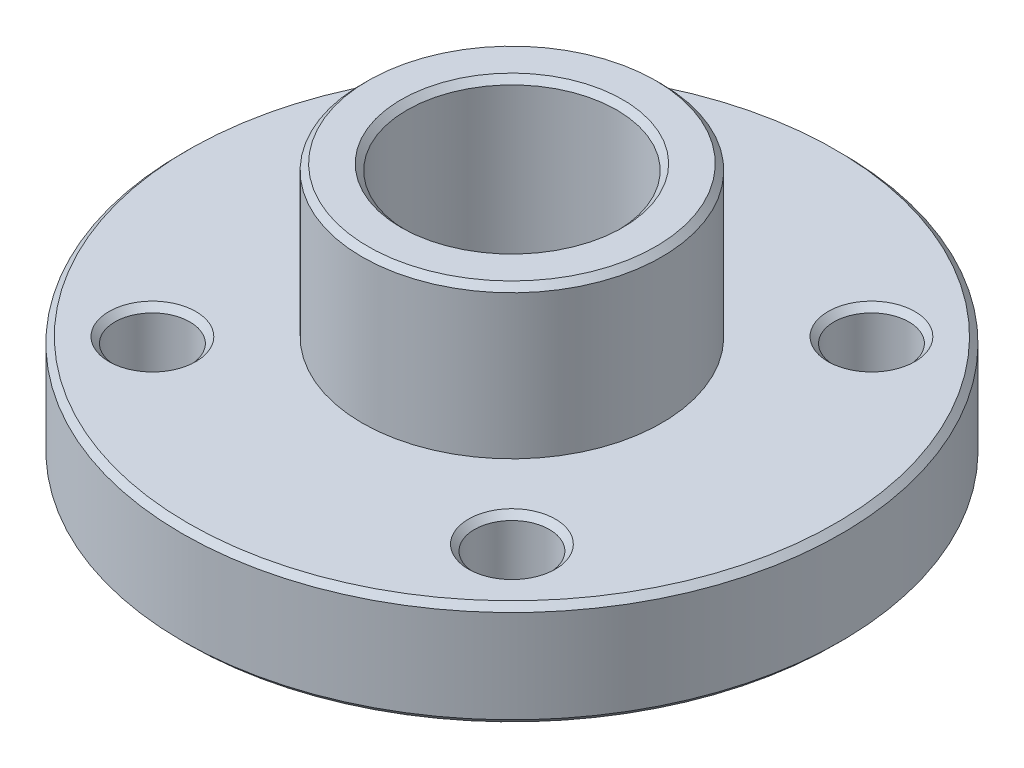
SolidWorks part; units mm, degrees
ref_plane "Front Plane" through (0, 0, 0) normal (0, 0, 1) x (1, 0, 0)
ref_plane "Top Plane" through (0, 0, 0) normal (0, 1, 0) x (1, 0, 0)
ref_plane "Right Plane" through (0, 0, 0) normal (1, 0, 0) x (0, 0, -1)
sketch "Sketch1" plane through (0, 0, 0) normal (0, 1, 0) x (1, 0, 0)
  circle A0 centre (0, 0) radius 5
  circle A1 centre (0, 0) radius 3.5
extrude "Boss-Extrude1" add sketch "Sketch1" along normal blind 10.5
ref_plane "Plane2" through (0, 2, 0) normal (0, 1, 0) x (1, 0, 0)
sketch "Sketch4" plane through (0, 2, 0) normal (0, 1, 0) x (1, 0, 0)
  circle A0 centre (0, 0) radius 5
  circle A1 centre (0, 0) radius 11
extrude "Boss-Extrude2" add sketch "Sketch4" along normal blind 3.5
sketch "Sketch5" plane through (0, 0, 0) normal (0, 1, 0) x (1, 0, 0)
  line L1 (-6, -6) -> (6, -6) construction
  line L2 (-6, -6) -> (-6, 6) construction
  line L3 (-6, 6) -> (6, 6) construction
  line L4 (6, -6) -> (6, 6) construction
  line L5 (-6, -6) -> (6, 6) construction
  line L6 (-6, 6) -> (6, -6) construction
  circle A0 centre (-6, 6) radius 1.25
  circle A1 centre (6, 6) radius 1.25
  circle A2 centre (6, -6) radius 1.25
  circle A3 centre (-6, -6) radius 1.25
  point P0 (0, 0)
extrude "Cut-Extrude2" cut sketch "Sketch5" along normal through all
chamfer "Chamfer1" distance 0.2 angle 45 14 edges at (0, 0, 3.5) (0, 0, 5) (0, 10.5, 3.5) (0, 10.5, 5) (0, 2, 11) (0, 5.5, 11) (6, 2, -4.75) (6, 2, 7.25) (-6, 2, 7.25) (-6, 2, -4.75) (-6, 5.5, -4.75) (6, 5.5, -4.75) (6, 5.5, 7.25) (-6, 5.5, 7.25)
